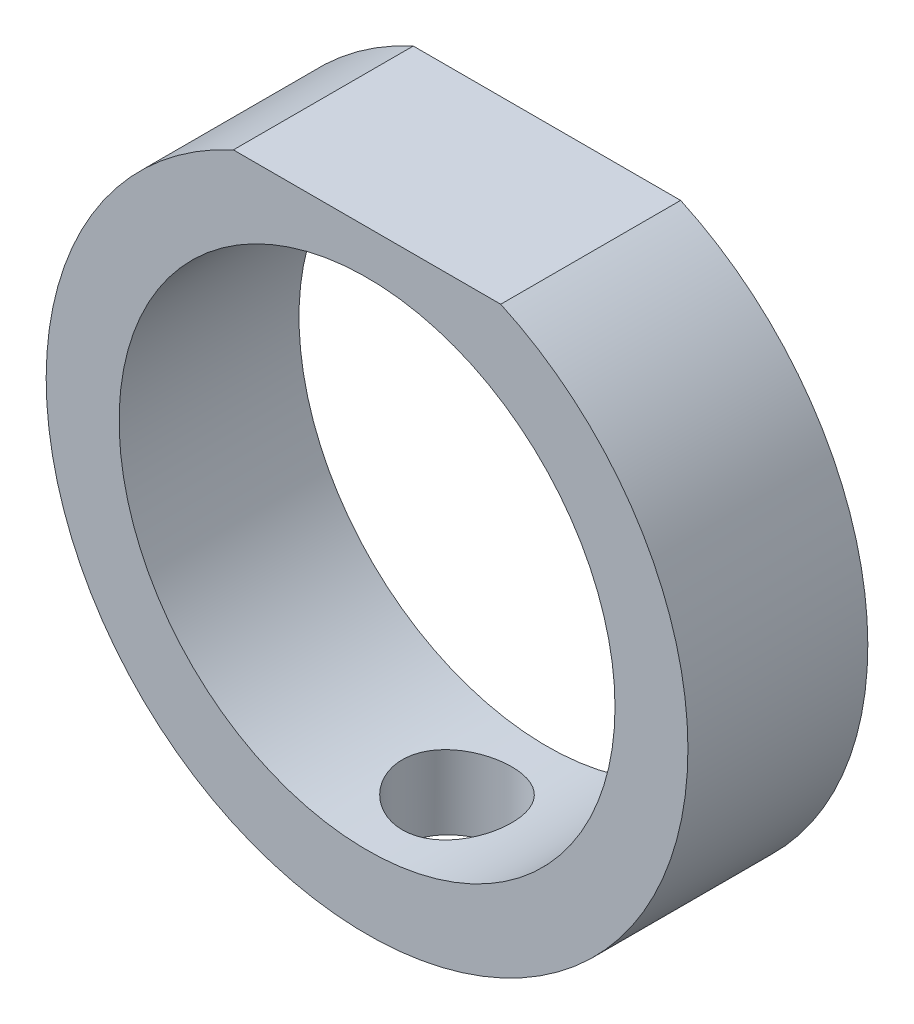
SolidWorks part; units mm, degrees
ref_plane "Front Plane" through (0, 0, 0) normal (0, 0, 1) x (1, 0, 0)
ref_plane "Top Plane" through (0, 0, 0) normal (0, 1, 0) x (1, 0, 0)
ref_plane "Right Plane" through (0, 0, 0) normal (1, 0, 0) x (0, 0, -1)
sketch "Sketch1" plane through (0, 0, 0) normal (0, 0, 1) x (1, 0, 0)
  line L0 (5.4991, 12) -> (-5.4991, 12)
  circle A0 centre (0, 0) radius 10.2
  arc A1 (-5.4991, 12) -> (5.4991, 12) centre (0, 0) ccw
  circle A3 centre (0, 0) radius 13.2 construction
  point P7 (12.6232, 3.8593)
  dimension "D1" = 20.4
  dimension "D3" = 12
  dimension "D2" = 3
extrude "Boss-Extrude1" add sketch "Sketch1" along normal blind 7.4
sketch "Sketch2" plane through (0, 0, 0) normal (0, 1, 0) x (1, 0, 0)
  line L0 (0, 4.1802) -> (0, -11.4667) construction
  circle A0 centre (0, -3.7) radius 2.25
  dimension "D1" = 4.5
  dimension "D2" = 3.7
extrude "Cut-Extrude1" cut sketch "Sketch2" against normal through all
